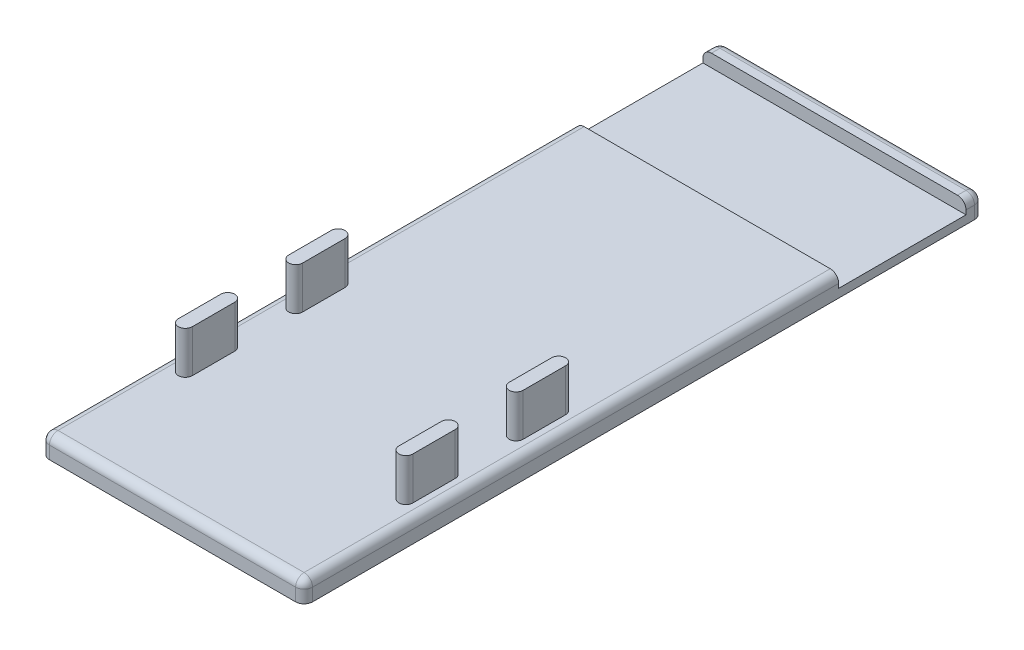
SolidWorks part; units mm, degrees
ref_plane "Front Plane" through (0, 0, 0) normal (0, 0, 1) x (1, 0, 0)
ref_plane "Top Plane" through (0, 0, 0) normal (0, 1, 0) x (1, 0, 0)
ref_plane "Right Plane" through (0, 0, 0) normal (1, 0, 0) x (0, 0, -1)
sketch "Sketch1" plane through (0, 0, 0) normal (0, 1, 0) x (1, 0, 0)
  line L1 (0, 0) -> (78.74, 0)
  line L2 (0, 0) -> (0, -203.2)
  line L3 (0, -203.2) -> (78.74, -203.2)
  line L4 (78.74, 0) -> (78.74, -203.2)
  dimension "D1" = 203.2
  dimension "D2" = 78.74
extrude "Boss-Extrude1" add sketch "Sketch1" along normal blind 6.35
sketch "Sketch2" plane through (0, 6.35, 0) normal (0, 1, 0) x (1, 0, 0)
  line L0 (78.74, 0) -> (0, 0) construction
  line L1 (6.3754, -133.35) -> (6.3754, -120.65) construction
  line L2 (4.2926, -133.35) -> (4.2926, -120.65)
  line L3 (39.37, -355.6) -> (39.37, 0) construction
  line L4 (8.4582, -133.35) -> (8.4582, -120.65)
  arc A1 (4.2926, -133.35) -> (8.4582, -133.35) centre (6.3754, -133.35) ccw
  arc A2 (8.4582, -120.65) -> (4.2926, -120.65) centre (6.3754, -120.65) ccw
  point P0 (0, 0)
  point P4 (72.3646, -127)
  point P7 (6.3754, -127)
  dimension "D1" = 127
  dimension "D2" = 65.9892
  dimension "D3" = 4.1656
  dimension "D5" = 12.7
extrude "Boss-Extrude2" add sketch "Sketch2" along normal blind 12.7
thread "Thread1" [suppressed] pitch 0.7937 start angle 0, offset 0, length 0, pitch 0.7937, diameter 4.1656
ref_plane "Plane1" through (8.4582, 12.7, 106.2482) normal (0, 0, 1) x (1, 0, 0)
sketch "Thread Profile1" plane through (8.4582, 12.7, 106.2482) normal (0, 0, 1) x (1, 0, 0)
  line L0 (0, 0) -> (0, 0.7937) construction
  line L11 (0, 0) -> (0, 0.6945)
  line L12 (0, 0.6945) -> (-0.4296, 0.4465)
  line L13 (-0.4296, 0.4465) -> (-0.4296, 0.248)
  line L15 (-0.4296, 0.248) -> (0, 0)
  line L17 (-0.4296, 0.3473) -> (0, 0.3473) construction
  point P2 (0, 0)
  dimension "Pitch" = 0.7937
  dimension "Profile_Angle" = 60
  dimension "Profile_Land" = 0.1984
  dimension "Profile_Height" = 0.4296
pattern_linear "LPattern2" count 2 spacing 65.9892 along (1, 0, 0) count 2 spacing 33.02 along (0, 0, 1) of "Thread1", "Boss-Extrude2"
sketch "Sketch3" plane through (78.74, 0, 0) normal (1, 0, 0) x (0, 0, -1)
  line L1 (-203.2, 6.35) -> (0, 6.35) construction
  line L4 (0, 6.35) -> (0, 0) construction
  line L5 (-203.2, 0) -> (0, 0) construction
  line L10 (-5.08, 6.35) -> (-43.18, 6.35)
  line L11 (-5.08, 6.35) -> (-5.08, 2.54)
  line L13 (-5.08, 2.54) -> (-43.18, 2.54)
  line L14 (-43.18, 6.35) -> (-43.18, 2.54)
  point P0 (-52.6809, 2.54)
  dimension "D1" = 38.1
  dimension "D2" = 2.54
  dimension "D3" = 5.08
extrude "Cut-Extrude1" cut sketch "Sketch3" against normal through all
pattern_linear "LPattern1" [suppressed] count 4 spacing 6.35
fillet "Fillet1" radius 2.54 10 edges at (0, 6.35, 2.54) (78.74, 6.35, 2.54) (39.37, 6.35, 0) (0, 3.175, 0) (78.74, 3.175, 0) (0, 3.175, 203.2) (78.74, 3.175, 203.2) (0, 6.35, 123.19) (39.37, 6.35, 203.2) (78.74, 6.35, 123.19)
